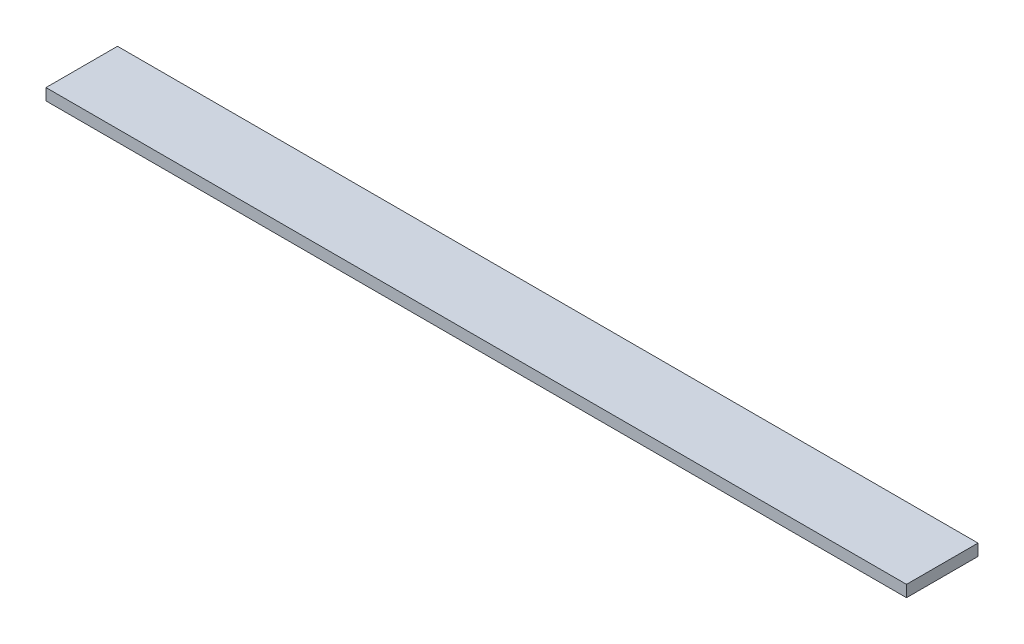
SolidWorks part; units mm, degrees
material "Pine"
ref_plane "Front Plane" through (0, 0, 0) normal (0, 0, 1) x (1, 0, 0)
ref_plane "Top Plane" through (0, 0, 0) normal (0, 1, 0) x (1, 0, 0)
ref_plane "Right Plane" through (0, 0, 0) normal (1, 0, 0) x (0, 0, -1)
sketch "Sketch1" plane through (0, 0, 0) normal (0, 1, 0) x (1, 0, 0)
  line L1 (-721.1739, 422.0587) -> (2106.1636, 422.0587)
  line L2 (-721.1739, 422.0587) -> (-721.1739, 187.1087)
  line L3 (-721.1739, 187.1087) -> (2106.1636, 187.1087)
  line L4 (2106.1636, 422.0587) -> (2106.1636, 187.1087)
  dimension "D1" = 234.95
  dimension "D2" = 2827.3375
extrude "Boss-Extrude1" add sketch "Sketch1" along normal blind 38.1 contours L1 L4 L3 L2
